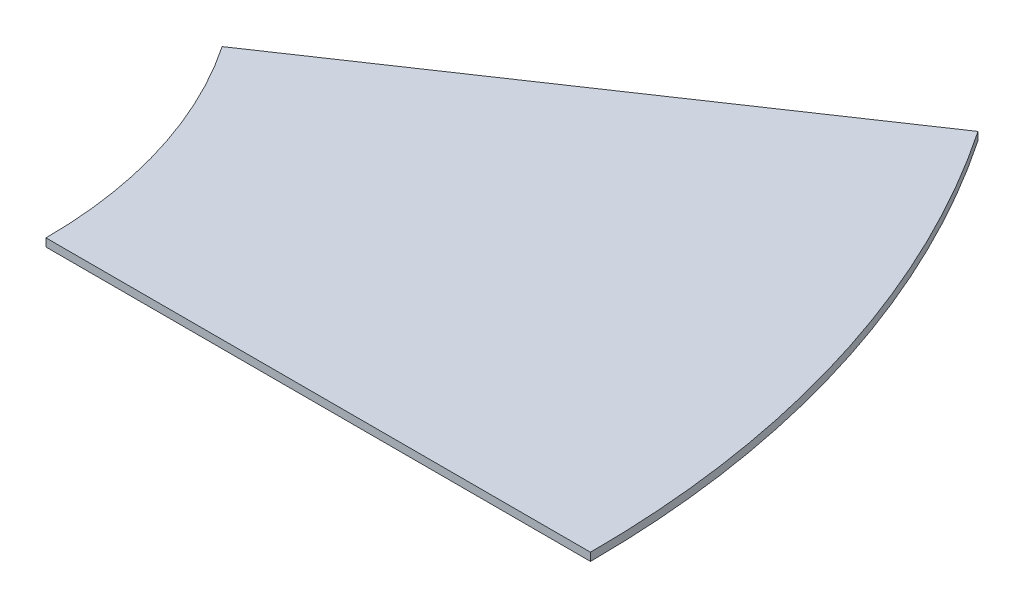
SolidWorks part; units mm, degrees
ref_plane "Front" through (0, 0, 0) normal (0, 0, 1) x (1, 0, 0)
ref_plane "Top" through (0, 0, 0) normal (0, 1, 0) x (1, 0, 0)
ref_plane "Right" through (0, 0, 0) normal (1, 0, 0) x (0, 0, -1)
sketch "草图1" plane through (0, 0, 0) normal (0, 1, 0) x (1, 0, 0)
  line L0 (0, 0) -> (110, 0) construction
  line L1 (91.1941, 61.5112) -> (0, 0) construction
  line L2 (91.1941, 61.5112) -> (41.4519, 27.9596)
  line L3 (110, 0) -> (50, 0)
  arc A0 (110, 0) -> (91.1941, 61.5112) centre (0, 0) ccw
  arc A1 (50, 0) -> (41.4519, 27.9596) centre (0, 0) ccw
  dimension "D2" = 50
  dimension "D3" = 110
  dimension "D1" = 34
extrude "凸台-拉伸1" add sketch "草图1" along normal blind 0.88 contours L3 A1 L2 A0
